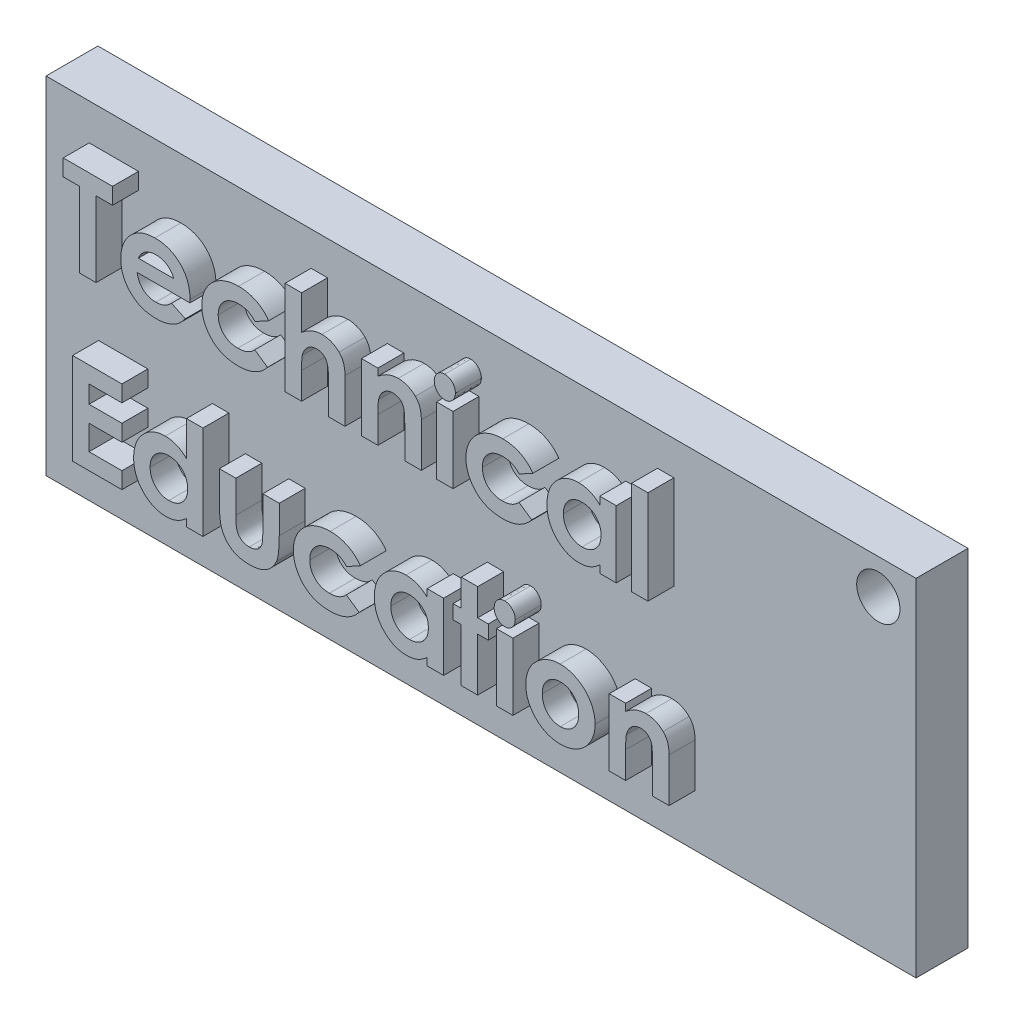
SolidWorks part; units mm, degrees
ref_plane "Front Plane" through (0, 0, 0) normal (0, 0, 1) x (1, 0, 0)
ref_plane "Top Plane" through (0, 0, 0) normal (0, 1, 0) x (1, 0, 0)
ref_plane "Right Plane" through (0, 0, 0) normal (1, 0, 0) x (0, 0, -1)
sketch "Sketch1" plane through (0, 0, 0) normal (0, 0, 1) x (1, 0, 0)
  line L1 (-23, -10) -> (23, -10)
  line L2 (-25, -8) -> (-25, 8)
  line L3 (-23, 10) -> (23, 10)
  line L4 (25, -8) -> (25, 8)
  line L5 (-25, -10) -> (25, 10) construction
  line L6 (-25, 10) -> (25, -10) construction
  arc A0 (25, 8) -> (23, 10) centre (23, 8) ccw
  arc A1 (25, -8) -> (23, -10) centre (23, -8) cw
  arc A2 (-23, -10) -> (-25, -8) centre (-23, -8) cw
  arc A3 (-23, 10) -> (-25, 8) centre (-23, 8) ccw
  point P0 (0, 0)
  dimension "D3" = 2
  dimension "D1" = 20
  dimension "D2" = 50
extrude "Boss-Extrude1" add sketch "Sketch1" along normal blind 3
sketch "Sketch3" plane through (0, 0, 3) normal (0, 0, 1) x (1, 0, 0)
  text T0 "Technical\r\nEducation" font "Century Gothic" height in points 20
extrude "Boss-Extrude2" add sketch "Sketch3" along normal blind 1.5
sketch "Sketch4" plane through (0, 0, 3) normal (0, 0, 1) x (1, 0, 0)
  circle A0 centre (23, 8) radius 1.25
  dimension "D1" = 2.5
extrude "Cut-Extrude1" cut sketch "Sketch4" against normal blind 41.5
sketch "Sketch6" plane through (0, 0, 0) normal (0, 0, -1) x (-1, 0, 0)
  line L1 (25.1353, 10) -> (-25.1353, 10)
  line L2 (25.1353, 10) -> (25.1353, -10)
  line L3 (25.1353, -10) -> (-25.1353, -10)
  line L4 (-25.1353, 10) -> (-25.1353, -10)
  line L5 (25.1353, 10) -> (-25.1353, -10) construction
  line L6 (25.1353, -10) -> (-25.1353, 10) construction
  point P0 (0, 0)
extrude "Boss-Extrude3" add sketch "Sketch6" against normal blind 3
sketch "Sketch7" plane through (0, 0, 3) normal (0, 0, 1) x (1, 0, 0)
  circle A0 centre (22.9546, 7.9869) radius 1.25
  dimension "D1" = 2.5
extrude "Cut-Extrude2" cut sketch "Sketch7" against normal blind 3
